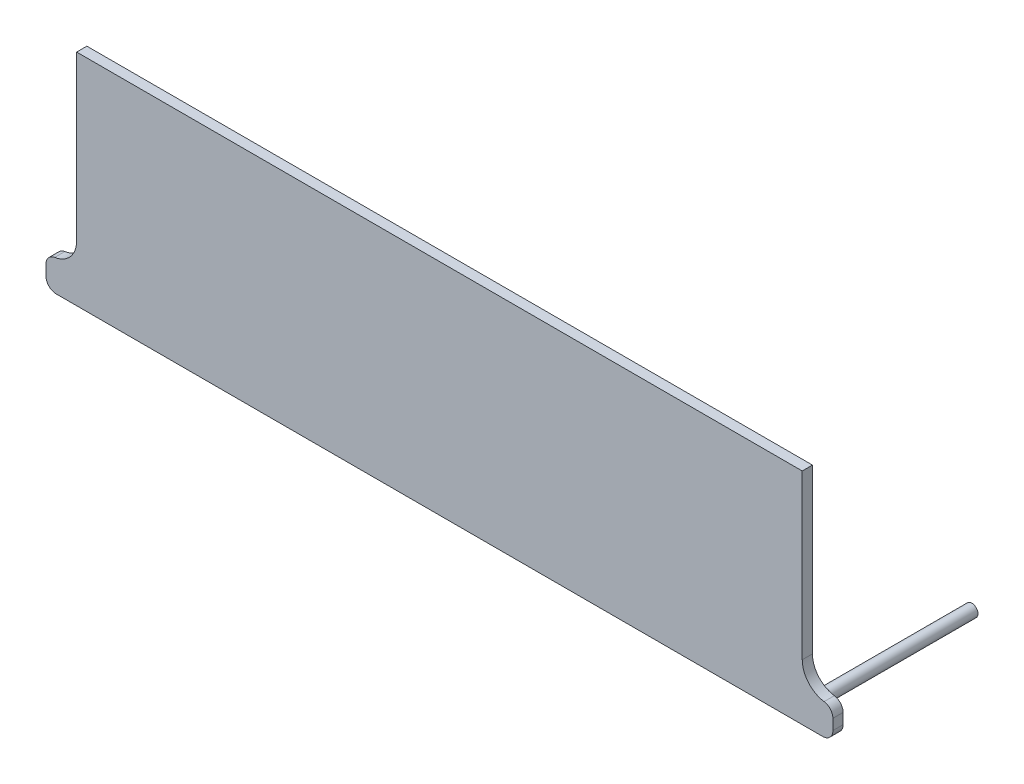
SolidWorks part; units mm, degrees
ref_plane "Front Plane" through (0, 0, 0) normal (0, 0, 1) x (1, 0, 0)
ref_plane "Top Plane" through (0, 0, 0) normal (0, 1, 0) x (1, 0, 0)
ref_plane "Right Plane" through (0, 0, 0) normal (1, 0, 0) x (0, 0, -1)
sketch "Sketch1" plane through (0, 0, 0) normal (0, 0, 1) x (1, 0, 0)
  line L0 (-355, -107.5) -> (-385, -107.5)
  line L1 (-355, 107.5) -> (355, 107.5)
  line L2 (-355, 107.5) -> (-355, -77.5)
  line L3 (-355, -107.5) -> (355, -107.5)
  line L4 (355, 107.5) -> (355, -77.5)
  line L5 (-355, 107.5) -> (355, -107.5) construction
  line L6 (-355, -107.5) -> (355, 107.5) construction
  line L7 (-385, -107.5) -> (-385, -77.5)
  line L8 (-385, -77.5) -> (-355, -77.5)
  line L9 (355, -107.5) -> (385, -107.5)
  line L10 (385, -107.5) -> (385, -77.5)
  line L11 (385, -77.5) -> (355, -77.5)
  line L12 (-355, -77.5) -> (-355, -107.5) construction
  line L13 (355, -107.5) -> (355, -77.5) construction
  point P0 (0, 0)
  dimension "D1" = 710
  dimension "D2" = 215
  dimension "D3" = 30
  dimension "D4" = 30
extrude "Boss-Extrude1" add sketch "Sketch1" along normal mid plane 10
fillet "Fillet1" radius 25 2 edges at (355, -77.5, 0) (-355, -77.5, 0)
sketch "Sketch2" plane through (0, 0, -5) normal (0, 0, -1) x (-1, 0, 0)
  circle A4 centre (-358, -90.5) radius 6
  circle A5 centre (358, -90.5) radius 6
extrude "Boss-Extrude2" add sketch "Sketch2" along normal up to vertex (153 mm away)
fillet "Fillet2" radius 10 4 edges at (-385, -107.5, 0) (385, -107.5, 0) (-352, -90.5, -5) (364, -90.5, -5)
fillet "Fillet3" radius 10 2 edges at (-385, -77.5, 0) (385, -77.5, 0)
